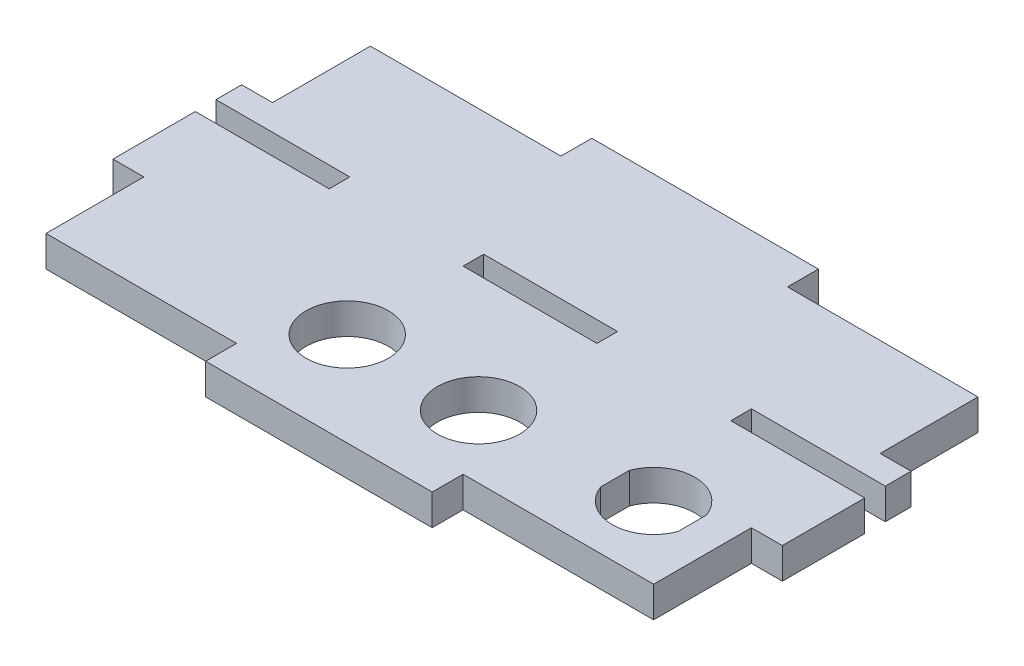
SolidWorks part; units mm, degrees
ref_plane "Front" through (0, 0, 0) normal (0, 0, 1) x (1, 0, 0)
ref_plane "Top" through (0, 0, 0) normal (0, 1, 0) x (1, 0, 0)
ref_plane "Right" through (0, 0, 0) normal (1, 0, 0) x (0, 0, -1)
sketch "Sketch1" plane through (0, 0, 0) normal (0, 1, 0) x (1, 0, 0)
  line L1 (0, 0) -> (130, 0)
  line L2 (0, 0) -> (0, 75)
  line L3 (0, 75) -> (130, 75)
  line L4 (130, 0) -> (130, 75)
  dimension "D1" = 130
  dimension "D2" = 75
extrude "Boss-Extrude1" add sketch "Sketch1" along normal blind 6
sketch "Sketch2" plane through (0, 6, 0) normal (0, 1, 0) x (1, 0, 0)
  line L0 (130, 0) -> (130, 75) construction
  line L1 (0, 0) -> (130, 0) construction
  circle A0 centre (52.25, 18.25) radius 8
  circle A1 centre (77.75, 18.25) radius 8
  dimension "D1" = 16
  dimension "D2" = 25.5
  dimension "D3" = 52.25
  dimension "D4" = 18.25
extrude "Cut-Extrude1" cut sketch "Sketch2" against normal through all
sketch "Sketch3" plane through (0, 6, 0) normal (0, 1, 0) x (1, 0, 0)
  line L5 (0, 75) -> (43, 75)
  line L18 (0, 75) -> (0, 69)
  line L19 (0, 75) -> (0, 0) construction
  line L20 (0, 45) -> (26, 45)
  line L21 (0, 45) -> (0, 41)
  line L22 (0, 41) -> (26, 41)
  line L23 (26, 45) -> (26, 41)
  line L24 (130, 0) -> (130, 75) construction
  line L25 (26, 45) -> (52, 45)
  line L26 (26, 45) -> (26, 41)
  line L27 (26, 41) -> (52, 41)
  line L28 (52, 45) -> (52, 41)
  line L29 (52, 41) -> (78, 41)
  line L30 (52, 41) -> (52, 45)
  line L31 (52, 45) -> (78, 45)
  line L32 (78, 41) -> (78, 45)
  line L33 (78, 45) -> (104, 45)
  line L34 (78, 45) -> (78, 41)
  line L35 (78, 41) -> (104, 41)
  line L36 (104, 45) -> (104, 41)
  line L37 (104, 41) -> (130, 41)
  line L38 (104, 41) -> (104, 45)
  line L39 (104, 45) -> (130, 45)
  line L40 (130, 41) -> (130, 45)
  line L41 (130, 75) -> (0, 75) construction
  line L42 (0, 69) -> (43, 69)
  line L43 (43, 75) -> (43, 69)
  line L44 (43, 69) -> (87, 69)
  line L45 (43, 69) -> (43, 75)
  line L46 (43, 75) -> (87, 75)
  line L47 (87, 69) -> (87, 75)
  line L48 (87, 69) -> (130, 69)
  line L49 (87, 69) -> (87, 75)
  line L50 (87, 75) -> (130, 75)
  line L51 (130, 69) -> (130, 75)
  line L52 (0, 0) -> (6, 0)
  line L53 (0, 0) -> (0, 25)
  line L54 (0, 25) -> (6, 25)
  line L55 (6, 0) -> (6, 25)
  line L56 (0, 25) -> (6, 25)
  line L57 (0, 25) -> (0, 50)
  line L58 (0, 50) -> (6, 50)
  line L59 (6, 25) -> (6, 50)
  line L60 (0, 50) -> (6, 50)
  line L61 (0, 50) -> (0, 75)
  line L62 (0, 75) -> (6, 75)
  line L63 (6, 50) -> (6, 75)
  line L64 (130, 75) -> (124, 75)
  line L65 (130, 75) -> (130, 50)
  line L66 (130, 50) -> (124, 50)
  line L67 (124, 75) -> (124, 50)
  line L68 (124, 50) -> (130, 50)
  line L69 (124, 50) -> (124, 25)
  line L70 (124, 25) -> (130, 25)
  line L71 (130, 50) -> (130, 25)
  line L72 (124, 25) -> (130, 25)
  line L73 (124, 25) -> (124, 0)
  line L74 (124, 0) -> (130, 0)
  line L75 (130, 25) -> (130, 0)
  line L77 (0, 0) -> (43, 0)
  line L78 (0, 0) -> (0, 6)
  line L79 (0, 6) -> (43, 6)
  line L80 (43, 0) -> (43, 6)
  line L81 (130, 0) -> (87, 0)
  line L82 (130, 0) -> (130, 6)
  line L83 (130, 6) -> (87, 6)
  line L84 (87, 0) -> (87, 6)
  line M11 (0, 75) -> (0, 0)
  line M13 (130, 0) -> (130, 75)
  dimension "D1" = 4
  dimension "D2" = 30
  dimension "D3" = 43
  dimension "D4" = 44
  dimension "D5" = 6
  dimension "D6" = 6
  dimension "D7" = 25
  dimension "D8" = 25
extrude "Cut-Extrude2" cut sketch "Sketch3" against normal through all contours L23 L20 L22 M11 | L29 L32 L31 L28 | L39 L36 L37 M13 | L18 L5 L43 L42 | L49 L48 L51 L50 | L61 L60 L63 L62 | L53 L52 L55 L54 | L73 L72 L75 L74 | L65 L64 L67 L66 | L78 L77 L80 L79 | L82 L81 L84 L83
sketch "Sketch4" plane through (0, 6, 0) normal (0, 1, 0) x (1, 0, 0)
  line L0 (130, 45) -> (130, 50) construction
  line L1 (102.5, 27.5) -> (117.5, 27.5)
  line L2 (102.5, 27.5) -> (102.5, 12.5)
  line L3 (102.5, 12.5) -> (117.5, 12.5)
  line L4 (117.5, 27.5) -> (117.5, 12.5)
  line L5 (102.5, 27.5) -> (117.5, 12.5) construction
  line L6 (102.5, 12.5) -> (117.5, 27.5) construction
  line L7 (87, 75) -> (43, 75) construction
  circle A0 centre (110, 20) radius 8
  dimension "D1" = 16
  dimension "D2" = 15
  dimension "D3" = 20
  dimension "D4" = 55
extrude "Cut-Extrude3" cut sketch "Sketch4" against normal through all contours L3 A0 L4 L1 L2 | L1 A0 | L3 A0
